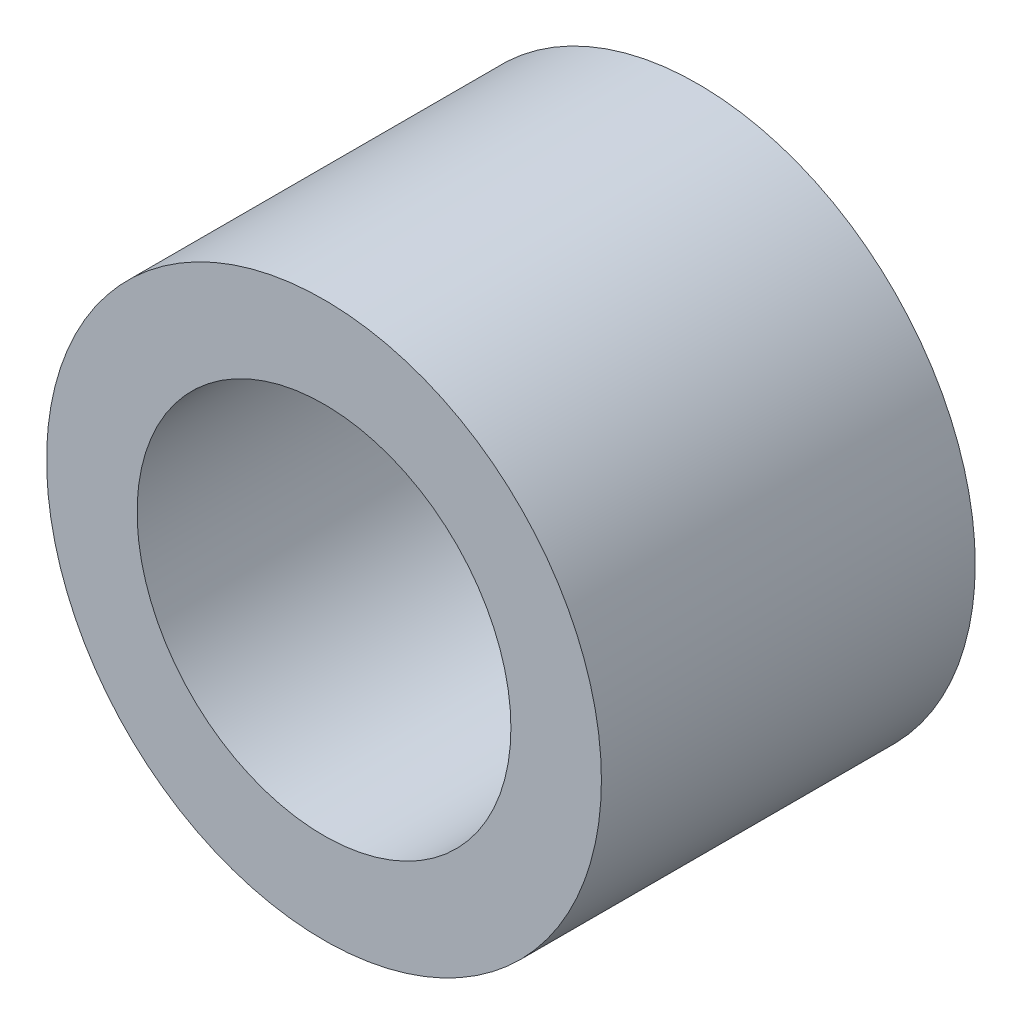
SolidWorks part; units mm, degrees
ref_plane "Front Plane" through (0, 0, 0) normal (0, 0, 1) x (1, 0, 0)
ref_plane "Top Plane" through (0, 0, 0) normal (0, 1, 0) x (1, 0, 0)
ref_plane "Right Plane" through (0, 0, 0) normal (1, 0, 0) x (0, 0, -1)
sketch "Sketch1" plane through (0, 0, 0) normal (0, 0, 1) x (1, 0, 0)
  circle A0 centre (0, 0) radius 6.35
  circle A1 centre (0, 0) radius 9.4245
extrude "Extrude1" add sketch "Sketch1" against normal blind 12.7
